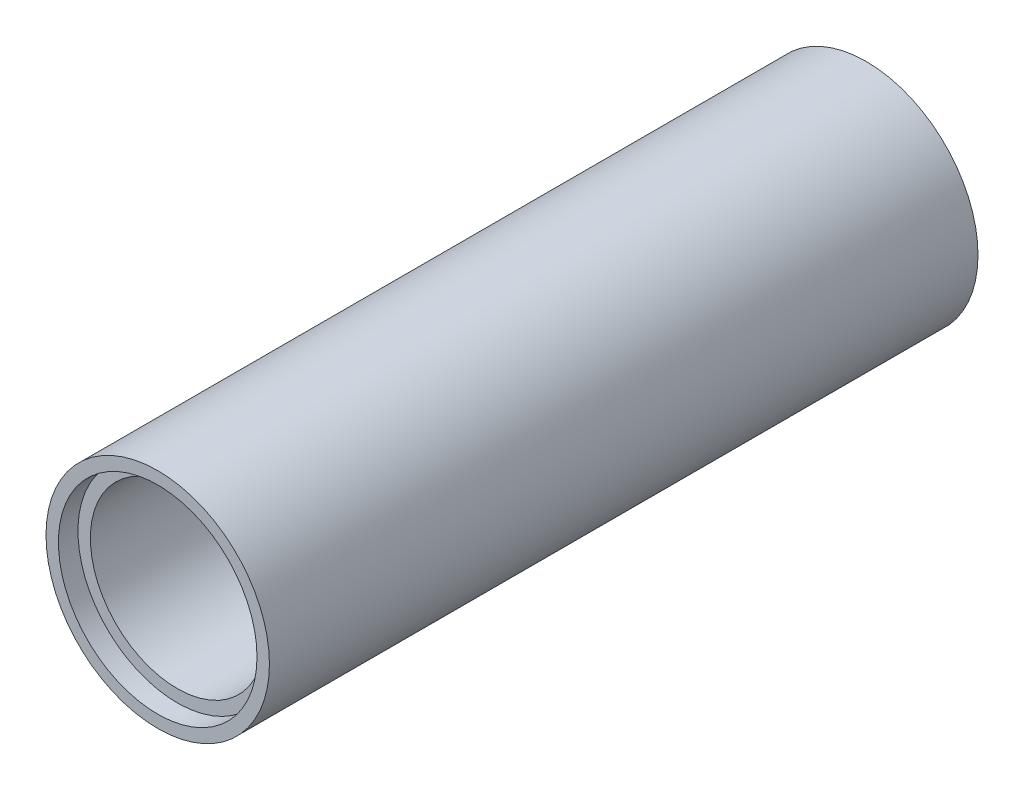
SolidWorks part; units mm, degrees
ref_plane "Płaszczyzna przednia" through (0, 0, 0) normal (0, 0, 1) x (1, 0, 0)
ref_plane "Płaszczyzna górna" through (0, 0, 0) normal (0, 1, 0) x (1, 0, 0)
ref_plane "Płaszczyzna prawa" through (0, 0, 0) normal (1, 0, 0) x (0, 0, -1)
sketch "Szkic1" plane through (0, 0, 0) normal (0, 0, 1) x (1, 0, 0)
  circle A0 centre (0, 0) radius 57.15
  circle A1 centre (0, 0) radius 44.45
  dimension "D1" = 114.3
  dimension "D2" = 88.9
extrude "Dodanie-wyciągnięcie1" add sketch "Szkic1" along normal blind 362.5
sketch "Szkic2" plane through (0, 0, 362.5) normal (0, 0, 1) x (1, 0, 0)
  circle A0 centre (0, 0) radius 50.8
  circle A1 centre (0, 0) radius 44.45 construction
  circle A2 centre (0, 0) radius 44.45
  dimension "D1" = 101.6
extrude "Wytnij-wyciągnięcie1" cut sketch "Szkic2" against normal blind 10
